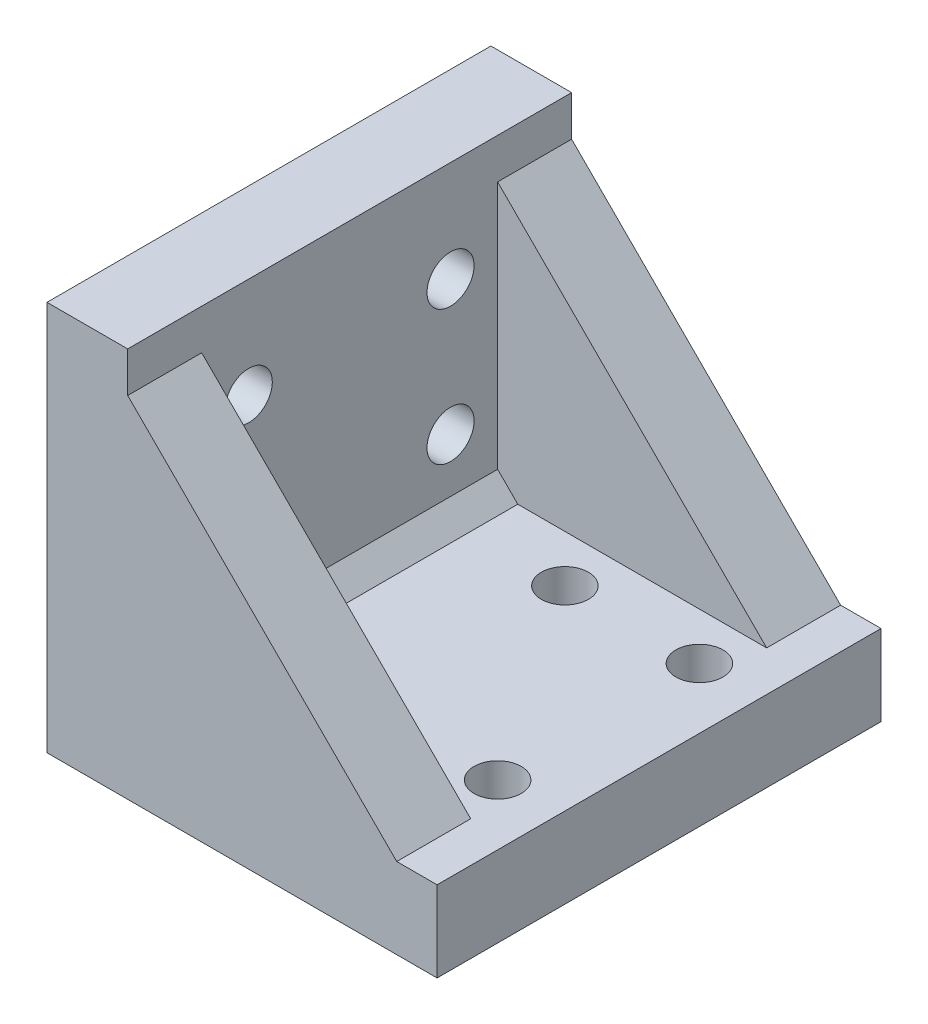
SolidWorks part; units mm, degrees
ref_plane "前视基准面" through (0, 0, 0) normal (0, 0, 1) x (1, 0, 0)
ref_plane "上视基准面" through (0, 0, 0) normal (0, 1, 0) x (1, 0, 0)
ref_plane "右视基准面" through (0, 0, 0) normal (1, 0, 0) x (0, 0, -1)
sketch "Sketch1" plane through (0, 0, 0) normal (0, 0, 1) x (1, 0, 0)
  line L0 (0, 0) -> (0, 29)
  line L1 (0, 29) -> (6, 29)
  line L2 (6, 29) -> (6, 6)
  line L3 (6, 6) -> (29, 6)
  line L4 (29, 6) -> (29, 0)
  line L5 (29, 0) -> (0, 0)
  dimension "D1" = 6
  dimension "D2" = 23
  dimension "D3" = 23
extrude "Boss-Extrude1" add sketch "Sketch1" along normal mid plane 33
sketch "Sketch2" plane through (6, 0, 0) normal (1, 0, 0) x (0, 0, -1)
  line L0 (-16.5, 29) -> (16.5, 4) construction
  line L1 (16.5, 6) -> (16.5, 29) construction
  line L3 (-7.5, 21.5) -> (7.5, 21.5) construction
  line L4 (-7.5, 21.5) -> (-7.5, 11.5) construction
  line L5 (-7.5, 11.5) -> (7.5, 11.5) construction
  line L6 (7.5, 21.5) -> (7.5, 11.5) construction
  line L7 (0, 11.5) -> (0, 21.5) construction
  line L8 (-7.5, 16.5) -> (7.5, 16.5) construction
  circle A0 centre (7.5, 21.5) radius 1.75
  circle A1 centre (7.5, 11.5) radius 1.75
  circle A2 centre (-7.5, 11.5) radius 1.75
  circle A3 centre (-7.5, 21.5) radius 1.75
  point P5 (0, 16.5)
  dimension "D3" = 3.5
  dimension "D1" = 10
  dimension "D2" = 15
extrude "Cut-Extrude1" cut sketch "Sketch2" against normal up to next
sketch "Sketch6" plane through (0, 6, 0) normal (0, 1, 0) x (1, 0, 0)
  line L2 (14.5, -7.5) -> (24.5, -7.5) construction
  line L3 (14.5, -7.5) -> (14.5, 7.5) construction
  line L4 (14.5, 7.5) -> (24.5, 7.5) construction
  line L5 (24.5, -7.5) -> (24.5, 7.5) construction
  line L6 (19.5, 7.5) -> (19.5, -7.5) construction
  line L7 (14.5, 0) -> (24.5, 0) construction
  circle A0 centre (14.5, -7.5) radius 1.75
  circle A1 centre (14.5, 7.5) radius 1.75
  circle A2 centre (24.5, 7.5) radius 1.75
  circle A3 centre (24.5, -7.5) radius 1.75
  point P4 (19.5, 0)
  dimension "D3" = 3.5
  dimension "D1" = 15
  dimension "D2" = 10
extrude "Cut-Extrude2" cut sketch "Sketch6" against normal up to next
sketch "Sketch3" plane through (0, 0, 16.5) normal (0, 0, 1) x (1, 0, 0)
  line L0 (6, 26) -> (26, 6)
  line L1 (6, 6) -> (6, 29) construction
  line L2 (29, 6) -> (6, 6) construction
  line L3 (26, 6) -> (6, 6)
  line L4 (6, 6) -> (6, 26)
  dimension "D1" = 20
  dimension "D2" = 20
extrude "Boss-Extrude2" add sketch "Sketch3" against normal blind 5.5
mirror "Mirror1" about plane through (0, 0, 0) normal (0, 0, 1) of "Boss-Extrude2"
chamfer "Chamfer1" distance 1.5 angle 45 1 edges at (6, 6, 0)
